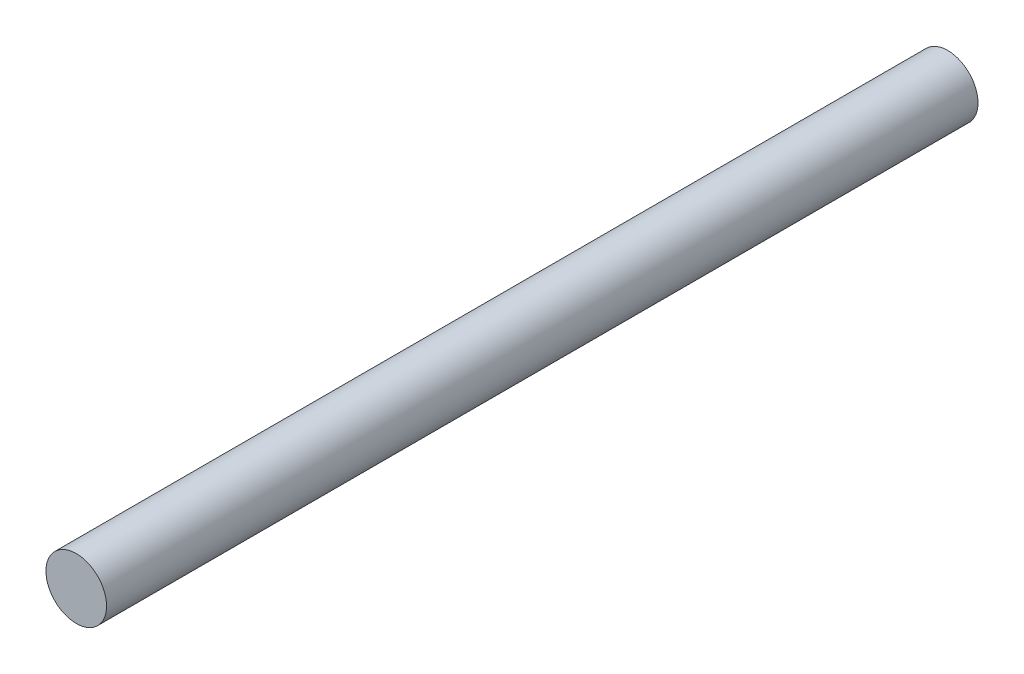
SolidWorks part; units mm, degrees
ref_plane "Front Plane" through (0, 0, 0) normal (0, 0, 1) x (1, 0, 0)
ref_plane "Top Plane" through (0, 0, 0) normal (0, 1, 0) x (1, 0, 0)
ref_plane "Right Plane" through (0, 0, 0) normal (1, 0, 0) x (0, 0, -1)
sketch "Sketch1" plane through (0, 0, 0) normal (0, 0, 1) x (1, 0, 0)
  circle A0 centre (0, 0) radius 4
  dimension "D1" = 8
extrude "Boss-Extrude1" add sketch "Sketch1" along normal blind 115
